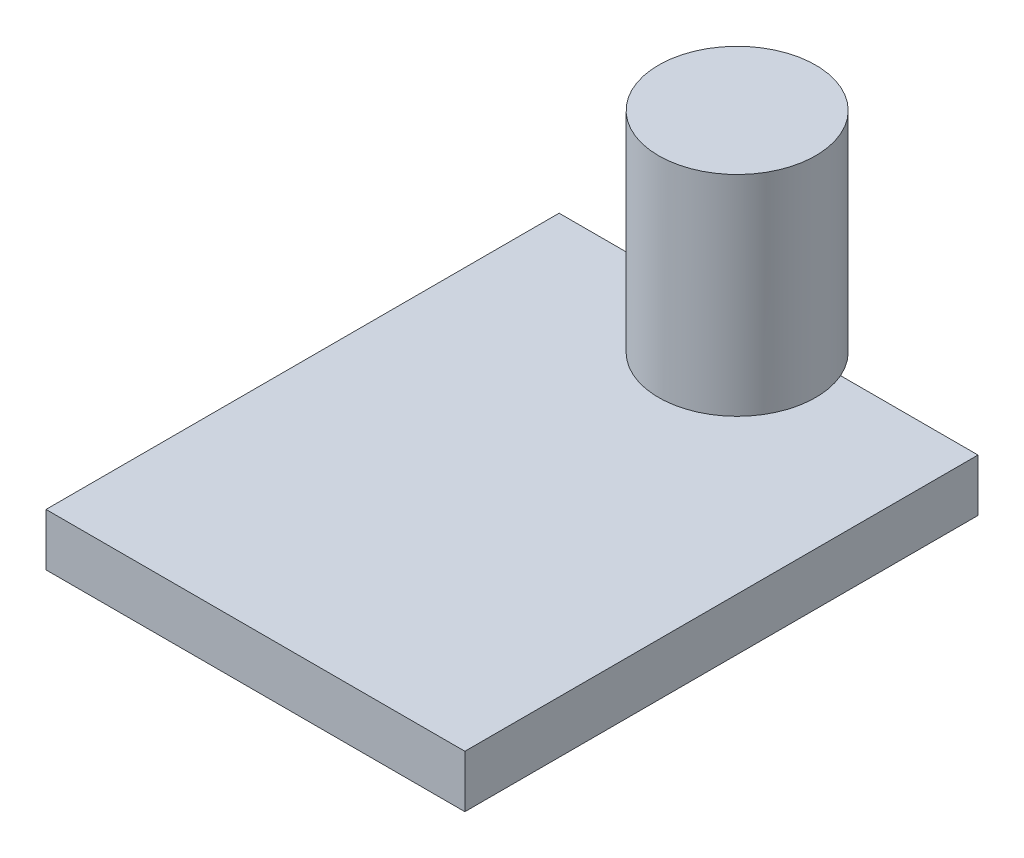
SolidWorks part; units mm, degrees
ref_plane "Front Plane" through (0, 0, 0) normal (0, 0, 1) x (1, 0, 0)
ref_plane "Top Plane" through (0, 0, 0) normal (0, 1, 0) x (1, 0, 0)
ref_plane "Right Plane" through (0, 0, 0) normal (1, 0, 0) x (0, 0, -1)
sketch "Sketch1" plane through (0, 0, 0) normal (0, 1, 0) x (1, 0, 0)
  line L1 (20, -24.5) -> (-20, -24.5)
  line L2 (20, -24.5) -> (20, 24.5)
  line L3 (20, 24.5) -> (-20, 24.5)
  line L4 (-20, -24.5) -> (-20, 24.5)
  line L5 (20, -24.5) -> (-20, 24.5) construction
  line L6 (20, 24.5) -> (-20, -24.5) construction
  point P0 (0, 0)
  dimension "D1" = 49
  dimension "D2" = 40
extrude "Boss-Extrude1" add sketch "Sketch1" along normal blind 5
sketch "Sketch2" plane through (0, 5, 0) normal (0, 1, 0) x (1, 0, 0)
  line L0 (20, 24.5) -> (-20, 24.5) construction
  circle A0 centre (0, 21.5) radius 7.5
  dimension "D1" = 15
  dimension "D2" = 3
extrude "Boss-Extrude2" add sketch "Sketch2" along normal blind 20
